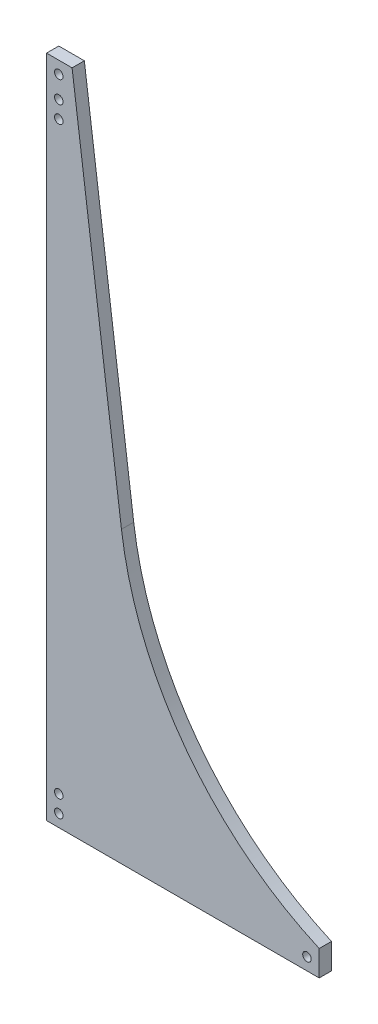
SolidWorks part; units mm, degrees
material "Maple"
ref_plane "Front Plane" through (0, 0, 0) normal (0, 0, 1) x (1, 0, 0)
ref_plane "Top Plane" through (0, 0, 0) normal (0, 1, 0) x (1, 0, 0)
ref_plane "Right Plane" through (0, 0, 0) normal (1, 0, 0) x (0, 0, -1)
sketch "Sketch1" plane through (0, 0, 0) normal (0, 0, 1) x (1, 0, 0)
  line L0 (0, 0) -> (406.4, 0)
  line L1 (0, 0) -> (0, 990.6)
  line L2 (0, 990.6) -> (38.1, 990.6)
  line L4 (406.4, 0) -> (406.4, 38.1)
  line L11 (38.1, 990.6) -> (111.6674, 431.8)
  line L12 (406.4, 38.1) -> (492.5345, 0) construction
  arc A0 (406.4, 38.1) -> (111.6674, 431.8) centre (609.539, 497.346) cw
  dimension "D1" = 990.6
  dimension "D2" = 406.4
  dimension "D3" = 38.1
  dimension "D4" = 38.1
  dimension "D5" = 97.5
  dimension "D6" = 558.8
extrude "Boss-Extrude1" add sketch "Sketch1" along normal mid plane 18.2562
sketch "Sketch2" plane through (0, 0, 9.1281) normal (0, 0, 1) x (1, 0, 0)
  line L0 (0, 990.6) -> (0, 0) construction
  line L1 (38.1, 990.6) -> (0, 990.6) construction
  line L2 (0, 0) -> (406.4, 0) construction
  line L3 (406.4, 0) -> (406.4, 38.1) construction
  line L6 (0, 990.6) -> (0, 0) construction
  line L7 (38.1, 990.6) -> (0, 990.6) construction
  circle A0 centre (18.2562, 972.3438) radius 6.35
  circle A1 centre (18.2562, 18.2562) radius 6.35
  circle A2 centre (388.1438, 18.2562) radius 6.35
  circle A4 centre (18.2562, 43.6562) radius 6.35
  circle A5 centre (18.2562, 939.8) radius 6.35
  circle A6 centre (18.2562, 914.4) radius 6.35
  dimension "D2" = 12.7
  dimension "D4" = 12.7
  dimension "D9" = 12.7
  dimension "D10" = 12.7
  dimension "D13" = 12.7
  dimension "D14" = 12.7
  dimension "D15" = 25.4
  dimension "D16" = 18.2562
  dimension "D17" = 50.8
  dimension "D18" = 18.2562
  dimension "D1" = 18.2562
  dimension "D3" = 18.2562
  dimension "D5" = 18.2562
  dimension "D6" = 18.2562
  dimension "D7" = 18.2562
  dimension "D8" = 18.2562
  dimension "D11" = 25.4
  dimension "D12" = 18.2562
extrude "Cut-Extrude1" cut sketch "Sketch2" against normal through all
